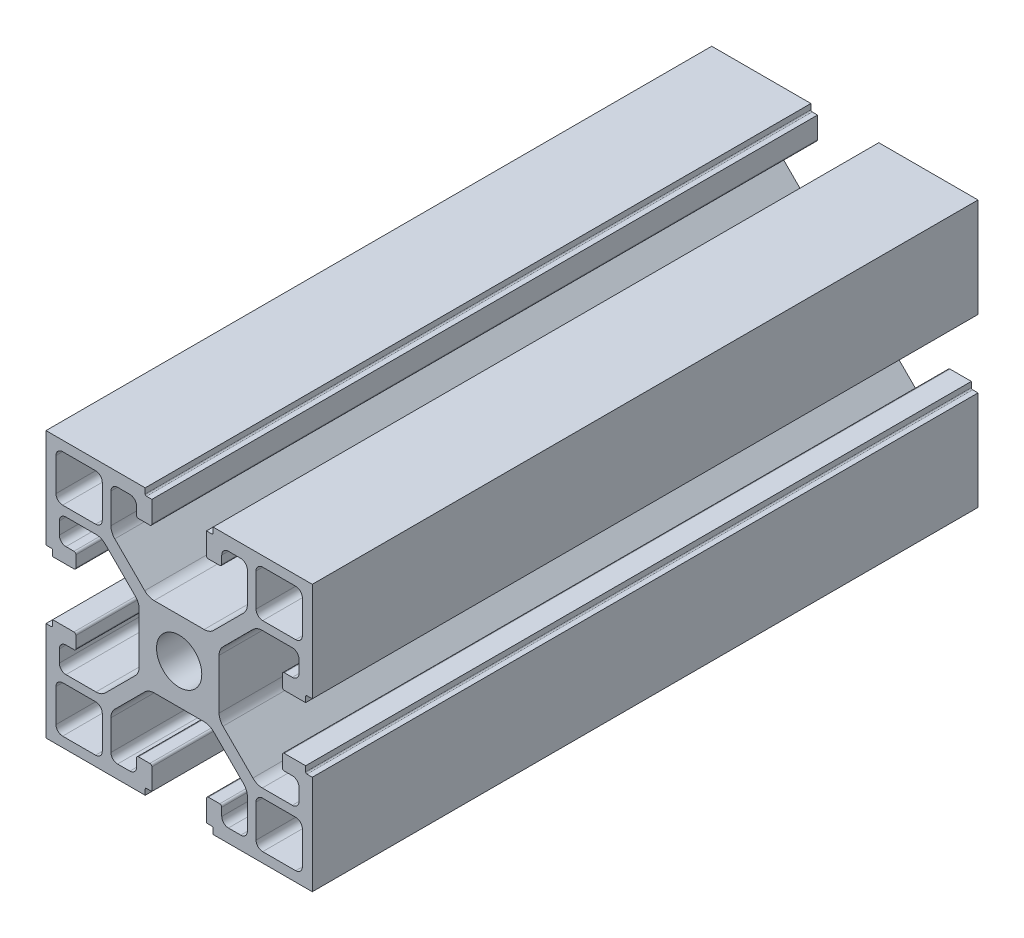
SolidWorks part; units mm, degrees
ref_plane "前视基准面" through (0, 0, 0) normal (0, 0, 1) x (1, 0, 0)
ref_plane "上视基准面" through (0, 0, 0) normal (0, 1, 0) x (1, 0, 0)
ref_plane "右视基准面" through (0, 0, 0) normal (1, 0, 0) x (0, 0, -1)
sketch "草图1" plane through (0, 0, 0) normal (0, 0, 1) x (1, 0, 0)
  line L0 (-4.6744, 18.9402) -> (-19.5744, 18.9402)
  line L1 (-19.5744, 18.9402) -> (-19.5744, 4.0402)
  line L2 (-3.6744, 17.9402) -> (-4.4744, 17.9402)
  line L3 (-4.6744, 18.1402) -> (-4.6744, 18.9402)
  line L4 (-19.5744, 4.0402) -> (-18.7744, 4.0402)
  line L5 (-18.5744, 3.8402) -> (-18.5744, 3.0402)
  line L6 (-12.067, 9.1902) -> (-16.5744, 9.1902)
  line L7 (-17.5744, 8.1902) -> (-17.5744, 6.3402)
  line L8 (-16.5744, 5.3402) -> (-15.3744, 5.3402)
  line L9 (-15.0744, 5.0402) -> (-15.0744, 3.3402)
  line L10 (-15.3744, 3.0402) -> (-18.5744, 3.0402)
  line L11 (-3.6744, 17.9402) -> (-3.6744, 14.7402)
  line L12 (-3.9744, 14.4402) -> (-5.6744, 14.4402)
  line L13 (-5.9744, 14.7402) -> (-5.9744, 15.9402)
  line L14 (-6.9744, 16.9402) -> (-8.8244, 16.9402)
  line L15 (-9.8244, 15.9402) -> (-9.8244, 11.4328)
  line L16 (-9.2386, 10.0186) -> (-4.746, 5.526)
  line L17 (-3.3318, 4.9402) -> (4.183, 4.9402)
  line L18 (6.4256, 2.6975) -> (6.4256, -4.8172)
  line L19 (4.183, -7.0598) -> (-3.3318, -7.0598)
  line L20 (-5.5744, -4.8172) -> (-5.5744, 2.6975)
  line L21 (-6.1602, 4.1118) -> (-10.6528, 8.6044)
  line L22 (17.9296, 17.4442) -> (12.9756, 17.4442)
  line L23 (-17.0784, 10.4902) -> (-12.1244, 10.4902)
  line L24 (-11.1244, 11.4902) -> (-11.1244, 16.4442)
  line L25 (-12.1244, 17.4442) -> (-17.0784, 17.4442)
  line L26 (17.9296, -19.5638) -> (12.9756, -19.5638)
  line L27 (-12.1244, -19.5638) -> (-17.0784, -19.5638)
  line L28 (4.5256, 17.9402) -> (5.3256, 17.9402)
  line L29 (5.5256, 18.1402) -> (5.5256, 18.9402)
  line L30 (20.4256, 4.0402) -> (19.6256, 4.0402)
  line L31 (19.4256, 3.8402) -> (19.4256, 3.0402)
  line L32 (12.9182, 9.1902) -> (17.4256, 9.1902)
  line L33 (18.4256, 8.1902) -> (18.4256, 6.3402)
  line L34 (17.4256, 5.3402) -> (16.2256, 5.3402)
  line L35 (15.9256, 5.0402) -> (15.9256, 3.3402)
  line L36 (16.2256, 3.0402) -> (19.4256, 3.0402)
  line L37 (4.5256, 17.9402) -> (4.5256, 14.7402)
  line L38 (4.8256, 14.4402) -> (6.5256, 14.4402)
  line L39 (6.8256, 14.7402) -> (6.8256, 15.9402)
  line L40 (7.8256, 16.9402) -> (9.6756, 16.9402)
  line L41 (10.6756, 15.9402) -> (10.6756, 11.4328)
  line L42 (10.0898, 10.0186) -> (5.5972, 5.526)
  line L43 (7.0114, 4.1118) -> (11.504, 8.6044)
  line L45 (17.9296, 10.4902) -> (12.9756, 10.4902)
  line L46 (11.9756, 11.4902) -> (11.9756, 16.4442)
  line L50 (-3.6744, -20.0598) -> (-4.4744, -20.0598)
  line L51 (-4.6744, -20.2598) -> (-4.6744, -21.0598)
  line L52 (-19.5744, -6.1598) -> (-18.7744, -6.1598)
  line L53 (-18.5744, -5.9598) -> (-18.5744, -5.1598)
  line L54 (-12.067, -11.3098) -> (-16.5744, -11.3098)
  line L55 (-17.5744, -10.3098) -> (-17.5744, -8.4598)
  line L56 (-16.5744, -7.4598) -> (-15.3744, -7.4598)
  line L57 (-15.0744, -7.1598) -> (-15.0744, -5.4598)
  line L58 (-15.3744, -5.1598) -> (-18.5744, -5.1598)
  line L59 (-3.6744, -20.0598) -> (-3.6744, -16.8598)
  line L60 (-3.9744, -16.5598) -> (-5.6744, -16.5598)
  line L61 (-5.9744, -16.8598) -> (-5.9744, -18.0598)
  line L62 (-6.9744, -19.0598) -> (-8.8244, -19.0598)
  line L63 (-9.8244, -18.0598) -> (-9.8244, -13.5525)
  line L64 (-9.2386, -12.1382) -> (-4.746, -7.6456)
  line L65 (-6.1602, -6.2314) -> (-10.6528, -10.724)
  line L67 (-17.0784, -12.6098) -> (-12.1244, -12.6098)
  line L68 (-11.1244, -13.6098) -> (-11.1244, -18.5638)
  line L72 (4.5256, -20.0598) -> (5.3256, -20.0598)
  line L73 (5.5256, -20.2598) -> (5.5256, -21.0598)
  line L74 (20.4256, -6.1598) -> (19.6256, -6.1598)
  line L75 (19.4256, -5.9598) -> (19.4256, -5.1598)
  line L76 (12.9182, -11.3098) -> (17.4256, -11.3098)
  line L77 (18.4256, -10.3098) -> (18.4256, -8.4598)
  line L78 (17.4256, -7.4598) -> (16.2256, -7.4598)
  line L79 (15.9256, -7.1598) -> (15.9256, -5.4598)
  line L80 (16.2256, -5.1598) -> (19.4256, -5.1598)
  line L81 (4.5256, -20.0598) -> (4.5256, -16.8598)
  line L82 (4.8256, -16.5598) -> (6.5256, -16.5598)
  line L83 (6.8256, -16.8598) -> (6.8256, -18.0598)
  line L84 (7.8256, -19.0598) -> (9.6756, -19.0598)
  line L85 (10.6756, -18.0598) -> (10.6756, -13.5525)
  line L86 (10.0898, -12.1382) -> (5.5972, -7.6456)
  line L87 (7.0114, -6.2314) -> (11.504, -10.724)
  line L89 (17.9296, -12.6098) -> (12.9756, -12.6098)
  line L90 (11.9756, -13.6098) -> (11.9756, -18.5638)
  line L94 (-18.0784, 11.4902) -> (-18.0784, 16.4442)
  line L96 (5.5256, 18.9402) -> (20.4256, 18.9402)
  line L99 (18.9296, 11.4902) -> (18.9296, 16.4442)
  line L101 (20.4256, 18.9402) -> (20.4256, 4.0402)
  line L102 (-4.6744, -21.0598) -> (-19.5744, -21.0598)
  line L103 (-19.5744, -21.0598) -> (-19.5744, -6.1598)
  line L106 (-18.0784, -13.6098) -> (-18.0784, -18.5638)
  line L108 (5.5256, -21.0598) -> (20.4256, -21.0598)
  line L111 (18.9296, -13.6098) -> (18.9296, -18.5638)
  line L113 (20.4256, -21.0598) -> (20.4256, -6.1598)
  arc A0 (-4.6744, 18.1402) -> (-4.4744, 17.9402) centre (-4.4744, 18.1402) ccw
  arc A1 (-18.5744, 3.8402) -> (-18.7744, 4.0402) centre (-18.7744, 3.8402) ccw
  arc A2 (-16.5744, 9.1902) -> (-17.5744, 8.1902) centre (-16.5744, 8.1902) ccw
  arc A3 (-17.5744, 6.3402) -> (-16.5744, 5.3402) centre (-16.5744, 6.3402) ccw
  arc A4 (-15.0744, 5.0402) -> (-15.3744, 5.3402) centre (-15.3744, 5.0402) ccw
  arc A5 (-15.3744, 3.0402) -> (-15.0744, 3.3402) centre (-15.3744, 3.3402) ccw
  arc A6 (-3.9744, 14.4402) -> (-3.6744, 14.7402) centre (-3.9744, 14.7402) ccw
  arc A7 (-5.9744, 14.7402) -> (-5.6744, 14.4402) centre (-5.6744, 14.7402) ccw
  arc A8 (-5.9744, 15.9402) -> (-6.9744, 16.9402) centre (-6.9744, 15.9402) ccw
  arc A9 (-8.8244, 16.9402) -> (-9.8244, 15.9402) centre (-8.8244, 15.9402) ccw
  arc A10 (-9.8244, 11.4328) -> (-9.2386, 10.0186) centre (-7.8244, 11.4328) ccw
  arc A11 (-4.746, 5.526) -> (-3.3318, 4.9402) centre (-3.3318, 6.9402) ccw
  arc A12 (-5.5744, 2.6975) -> (-6.1602, 4.1118) centre (-7.5744, 2.6975) ccw
  circle A13 centre (0.4256, -1.0598) radius 3.4
  arc A14 (-10.6528, 8.6044) -> (-12.067, 9.1902) centre (-12.067, 7.1902) ccw
  arc A15 (-18.0784, 11.4902) -> (-17.0784, 10.4902) centre (-17.0784, 11.4902) ccw
  arc A16 (-12.1244, 10.4902) -> (-11.1244, 11.4902) centre (-12.1244, 11.4902) ccw
  arc A17 (-11.1244, 16.4442) -> (-12.1244, 17.4442) centre (-12.1244, 16.4442) ccw
  arc A18 (5.3256, 17.9402) -> (5.5256, 18.1402) centre (5.3256, 18.1402) ccw
  arc A19 (19.6256, 4.0402) -> (19.4256, 3.8402) centre (19.6256, 3.8402) ccw
  arc A20 (18.4256, 8.1902) -> (17.4256, 9.1902) centre (17.4256, 8.1902) ccw
  arc A21 (17.4256, 5.3402) -> (18.4256, 6.3402) centre (17.4256, 6.3402) ccw
  arc A22 (16.2256, 5.3402) -> (15.9256, 5.0402) centre (16.2256, 5.0402) ccw
  arc A23 (15.9256, 3.3402) -> (16.2256, 3.0402) centre (16.2256, 3.3402) ccw
  arc A24 (4.5256, 14.7402) -> (4.8256, 14.4402) centre (4.8256, 14.7402) ccw
  arc A25 (6.5256, 14.4402) -> (6.8256, 14.7402) centre (6.5256, 14.7402) ccw
  arc A26 (7.8256, 16.9402) -> (6.8256, 15.9402) centre (7.8256, 15.9402) ccw
  arc A27 (10.6756, 15.9402) -> (9.6756, 16.9402) centre (9.6756, 15.9402) ccw
  arc A28 (10.0898, 10.0186) -> (10.6756, 11.4328) centre (8.6756, 11.4328) ccw
  arc A29 (4.183, 4.9402) -> (5.5972, 5.526) centre (4.183, 6.9402) ccw
  arc A30 (7.0114, 4.1118) -> (6.4256, 2.6975) centre (8.4256, 2.6975) ccw
  arc A31 (12.9182, 9.1902) -> (11.504, 8.6044) centre (12.9182, 7.1902) ccw
  arc A32 (17.9296, 10.4902) -> (18.9296, 11.4902) centre (17.9296, 11.4902) ccw
  arc A33 (11.9756, 11.4902) -> (12.9756, 10.4902) centre (12.9756, 11.4902) ccw
  arc A34 (12.9756, 17.4442) -> (11.9756, 16.4442) centre (12.9756, 16.4442) ccw
  arc A35 (-4.4744, -20.0598) -> (-4.6744, -20.2598) centre (-4.4744, -20.2598) ccw
  arc A36 (-18.7744, -6.1598) -> (-18.5744, -5.9598) centre (-18.7744, -5.9598) ccw
  arc A37 (-17.5744, -10.3098) -> (-16.5744, -11.3098) centre (-16.5744, -10.3098) ccw
  arc A38 (-16.5744, -7.4598) -> (-17.5744, -8.4598) centre (-16.5744, -8.4598) ccw
  arc A39 (-15.3744, -7.4598) -> (-15.0744, -7.1598) centre (-15.3744, -7.1598) ccw
  arc A40 (-15.0744, -5.4598) -> (-15.3744, -5.1598) centre (-15.3744, -5.4598) ccw
  arc A41 (-3.6744, -16.8598) -> (-3.9744, -16.5598) centre (-3.9744, -16.8598) ccw
  arc A42 (-5.6744, -16.5598) -> (-5.9744, -16.8598) centre (-5.6744, -16.8598) ccw
  arc A43 (-6.9744, -19.0598) -> (-5.9744, -18.0598) centre (-6.9744, -18.0598) ccw
  arc A44 (-9.8244, -18.0598) -> (-8.8244, -19.0598) centre (-8.8244, -18.0598) ccw
  arc A45 (-9.2386, -12.1382) -> (-9.8244, -13.5525) centre (-7.8244, -13.5525) ccw
  arc A46 (-3.3318, -7.0598) -> (-4.746, -7.6456) centre (-3.3318, -9.0598) ccw
  arc A47 (-6.1602, -6.2314) -> (-5.5744, -4.8172) centre (-7.5744, -4.8172) ccw
  arc A48 (-12.067, -11.3098) -> (-10.6528, -10.724) centre (-12.067, -9.3098) ccw
  arc A49 (-17.0784, -12.6098) -> (-18.0784, -13.6098) centre (-17.0784, -13.6098) ccw
  arc A50 (-11.1244, -13.6098) -> (-12.1244, -12.6098) centre (-12.1244, -13.6098) ccw
  arc A51 (-12.1244, -19.5638) -> (-11.1244, -18.5638) centre (-12.1244, -18.5638) ccw
  arc A52 (5.5256, -20.2598) -> (5.3256, -20.0598) centre (5.3256, -20.2598) ccw
  arc A53 (19.4256, -5.9598) -> (19.6256, -6.1598) centre (19.6256, -5.9598) ccw
  arc A54 (17.4256, -11.3098) -> (18.4256, -10.3098) centre (17.4256, -10.3098) ccw
  arc A55 (18.4256, -8.4598) -> (17.4256, -7.4598) centre (17.4256, -8.4598) ccw
  arc A56 (15.9256, -7.1598) -> (16.2256, -7.4598) centre (16.2256, -7.1598) ccw
  arc A57 (16.2256, -5.1598) -> (15.9256, -5.4598) centre (16.2256, -5.4598) ccw
  arc A58 (4.8256, -16.5598) -> (4.5256, -16.8598) centre (4.8256, -16.8598) ccw
  arc A59 (6.8256, -16.8598) -> (6.5256, -16.5598) centre (6.5256, -16.8598) ccw
  arc A60 (6.8256, -18.0598) -> (7.8256, -19.0598) centre (7.8256, -18.0598) ccw
  arc A61 (9.6756, -19.0598) -> (10.6756, -18.0598) centre (9.6756, -18.0598) ccw
  arc A62 (10.6756, -13.5525) -> (10.0898, -12.1382) centre (8.6756, -13.5525) ccw
  arc A63 (5.5972, -7.6456) -> (4.183, -7.0598) centre (4.183, -9.0598) ccw
  arc A64 (6.4256, -4.8172) -> (7.0114, -6.2314) centre (8.4256, -4.8172) ccw
  arc A65 (11.504, -10.724) -> (12.9182, -11.3098) centre (12.9182, -9.3098) ccw
  arc A66 (18.9296, -13.6098) -> (17.9296, -12.6098) centre (17.9296, -13.6098) ccw
  arc A67 (12.9756, -12.6098) -> (11.9756, -13.6098) centre (12.9756, -13.6098) ccw
  arc A68 (11.9756, -18.5638) -> (12.9756, -19.5638) centre (12.9756, -18.5638) ccw
  arc A71 (-17.0784, 17.4442) -> (-18.0784, 16.4442) centre (-17.0784, 16.4442) ccw
  arc A74 (18.9296, 16.4442) -> (17.9296, 17.4442) centre (17.9296, 16.4442) ccw
  arc A77 (-18.0784, -18.5638) -> (-17.0784, -19.5638) centre (-17.0784, -18.5638) ccw
  arc A80 (17.9296, -19.5638) -> (18.9296, -18.5638) centre (17.9296, -18.5638) ccw
extrude "凸台-拉伸1" add sketch "草图1" along normal blind 100
